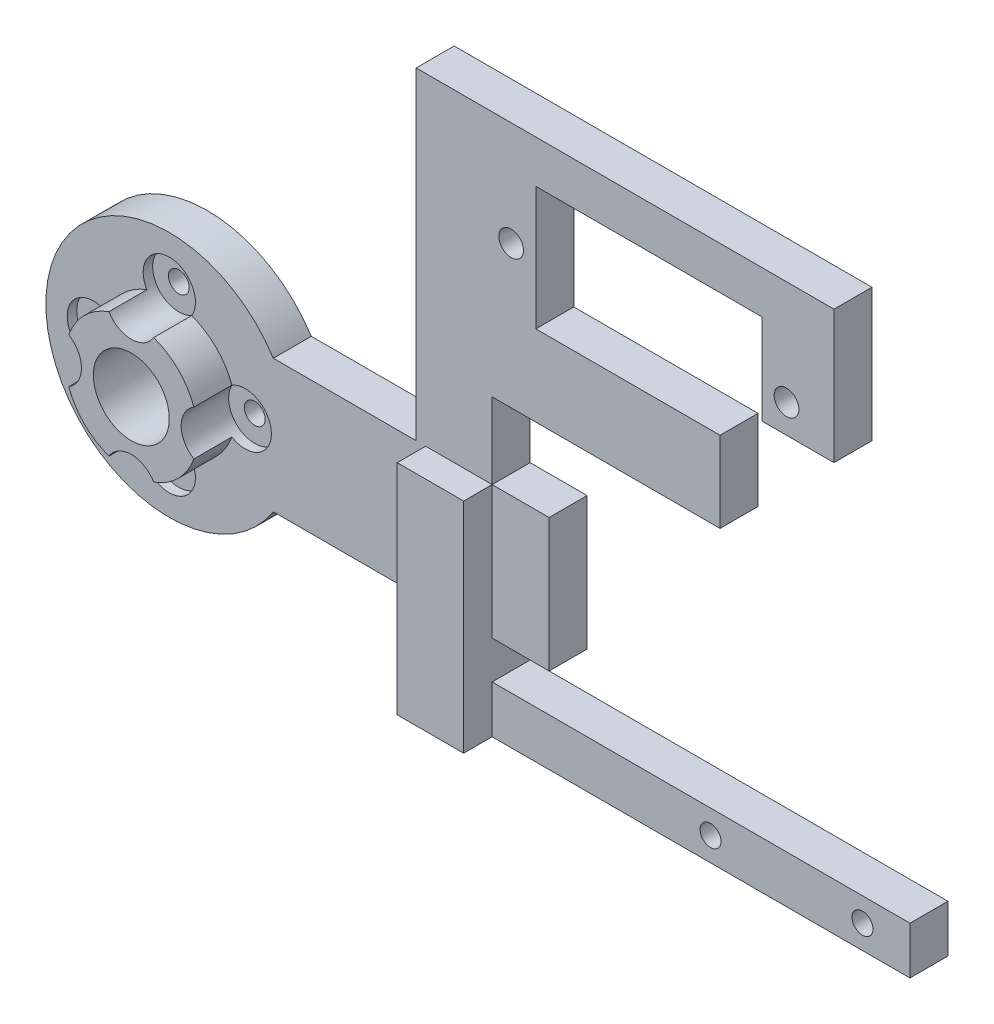
SolidWorks part; units mm, degrees
ref_plane "Front Plane" through (0, 0, 0) normal (0, 0, 1) x (1, 0, 0)
ref_plane "Top Plane" through (0, 0, 0) normal (0, 1, 0) x (1, 0, 0)
ref_plane "Right Plane" through (0, 0, 0) normal (1, 0, 0) x (0, 0, -1)
sketch "Elbow_horn_flange_profile" plane through (0, 0, 0) normal (0, 0, 1) x (1, 0, 0)
  circle A0 centre (0, 0) radius 13
  dimension "D1" = 26
extrude "Elbow_horn_flange" add sketch "Elbow_horn_flange_profile" along normal blind 4
sketch "Forearm_web_profile" plane through (0, 0, 0) normal (0, 0, 1) x (1, 0, 0)
  line L1 (0, -7) -> (40, -7)
  line L2 (0, -7) -> (0, 7)
  line L3 (0, 7) -> (40, 7)
  line L4 (40, -7) -> (40, 7)
  dimension "D1" = 40
  dimension "D2" = 14
  dimension "D3" = 7
extrude "Forearm_web" add sketch "Forearm_web_profile" along normal blind 4
sketch "Gripper_mount_rib_profile" plane through (0, 0, 0) normal (0, 0, 1) x (1, 0, 0)
  line L1 (26, 0) -> (34, 0)
  line L2 (26, 0) -> (26, 30)
  line L3 (26, 30) -> (34, 30)
  line L4 (34, 0) -> (34, 30)
  dimension "D1" = 8
  dimension "D2" = 30
  dimension "D3" = 26
extrude "Gripper_mount_rib" add sketch "Gripper_mount_rib_profile" along normal blind 4
sketch "Gripper_servo_mount_profile" plane through (0, 0, 0) normal (0, 0, 1) x (1, 0, 0)
  line L1 (26, 15) -> (70, 15)
  line L2 (26, 15) -> (26, 41)
  line L3 (26, 41) -> (70, 41)
  line L4 (70, 15) -> (70, 41)
  dimension "D1" = 44
  dimension "D2" = 26
  dimension "D3" = 26
  dimension "D4" = 15
extrude "Gripper_servo_mount" add sketch "Gripper_servo_mount_profile" along normal blind 4
sketch "Grip_SG90_body_clearance_profile" plane through (0, 0, 0) normal (0, 0, 1) x (1, 0, 0)
  line L1 (38.6, 23.5) -> (62.4, 23.5)
  line L2 (38.6, 23.5) -> (38.6, 36.5)
  line L3 (38.6, 36.5) -> (62.4, 36.5)
  line L4 (62.4, 23.5) -> (62.4, 36.5)
  dimension "D1" = 23.8
  dimension "D2" = 13
  dimension "D3" = 38.6
  dimension "D4" = 23.5
extrude "Grip_SG90_body_clearance" cut sketch "Grip_SG90_body_clearance_profile" along normal through all from offset 5
sketch "Moving_finger_sweep_relief_profile" plane through (0, 0, 0) normal (0, 0, 1) x (1, 0, 0)
  line L1 (58, 14) -> (71, 14)
  line L2 (58, 14) -> (58, 27)
  line L3 (58, 27) -> (71, 27)
  line L4 (71, 14) -> (71, 27)
  dimension "D1" = 13
  dimension "D2" = 13
  dimension "D3" = 58
  dimension "D4" = 14
extrude "Moving_finger_sweep_relief" cut sketch "Moving_finger_sweep_relief_profile" along normal through all from offset 5
sketch "Grip_servo_tab_fasteners_profile" plane through (0, 0, 0) normal (0, 0, 1) x (1, 0, 0)
  circle A0 centre (36, 30) radius 1.3
  circle A1 centre (65, 30) radius 1.3
  dimension "D1" = 2.6
  dimension "D2" = 2.6
  dimension "D3" = 36
  dimension "D4" = 65
  dimension "D5" = 30
extrude "Grip_servo_tab_fasteners" cut sketch "Grip_servo_tab_fasteners_profile" along normal through all from offset 50
sketch "Fixed_finger_spine_profile" plane through (0, 0, 0) normal (0, 0, 1) x (1, 0, 0)
  line L1 (30, -16) -> (78, -16)
  line L2 (30, -16) -> (30, -11)
  line L3 (30, -11) -> (78, -11)
  line L4 (78, -16) -> (78, -11)
  dimension "D1" = 48
  dimension "D2" = 5
  dimension "D3" = 30
  dimension "D4" = 11
extrude "Fixed_finger_spine" add sketch "Fixed_finger_spine_profile" along normal blind 4
sketch "Fixed_finger_root_profile" plane through (0, 0, 0) normal (0, 0, 1) x (1, 0, 0)
  line L1 (27, -16) -> (34, -16)
  line L2 (27, -16) -> (27, 7)
  line L3 (27, 7) -> (34, 7)
  line L4 (34, -16) -> (34, 7)
  dimension "D1" = 7
  dimension "D2" = 23
  dimension "D3" = 27
  dimension "D4" = 7
extrude "Fixed_finger_root" add sketch "Fixed_finger_root_profile" along normal blind 7
sketch "Elbow_center_screw_access_profile" plane through (0, 0, 0) normal (0, 0, 1) x (1, 0, 0)
  circle A0 centre (0, 0) radius 4
  dimension "D1" = 8
extrude "Elbow_center_screw_access" cut sketch "Elbow_center_screw_access_profile" along normal through all from offset 50
sketch "Elbow_dowel_support_hub_profile" plane through (0, 0, 0) normal (0, 0, 1) x (1, 0, 0)
  circle A0 centre (0, 0) radius 7
  circle A1 centre (0, 0) radius 4
  dimension "D1" = 14
  dimension "D2" = 8
extrude "Elbow_dowel_support_hub" add sketch "Elbow_dowel_support_hub_profile" along normal blind 4 from offset 4
sketch "Elbow_horn_fasteners_profile" plane through (0, 0, 0) normal (0, 0, 1) x (1, 0, 0)
  circle A0 centre (0, -8) radius 1.1
  circle A1 centre (0, 8) radius 1.1
  circle A2 centre (-8, 0) radius 1.1
  circle A3 centre (8, 0) radius 1.1
  dimension "D1" = 2.2
  dimension "D2" = 2.2
  dimension "D3" = 2.2
  dimension "D4" = 2.2
  dimension "D5" = 8
  dimension "D6" = 8
  dimension "D7" = 8
  dimension "D8" = 8
extrude "Elbow_horn_fasteners" cut sketch "Elbow_horn_fasteners_profile" along normal through all from offset 50
sketch "Elbow_horn_washer_recess_profile" plane through (0, 0, 0) normal (0, 0, 1) x (1, 0, 0)
  circle A0 centre (0, -8) radius 2.75
  circle A1 centre (0, 8) radius 2.75
  circle A2 centre (-8, 0) radius 2.75
  circle A3 centre (8, 0) radius 2.75
  dimension "D1" = 5.5
  dimension "D2" = 5.5
  dimension "D3" = 5.5
  dimension "D4" = 5.5
  dimension "D5" = 8
  dimension "D6" = 8
  dimension "D7" = 8
  dimension "D8" = 8
extrude "M2x8_washer_and_hub_clearance" cut sketch "Elbow_horn_washer_recess_profile" along normal blind 5 from offset 3
sketch "Fixed_pad_keeper_fasteners_profile" plane through (0, 0, 0) normal (0, 0, 1) x (1, 0, 0)
  circle A0 centre (57, -13.5) radius 1.1
  circle A1 centre (73, -13.5) radius 1.1
  dimension "D1" = 2.2
  dimension "D2" = 2.2
  dimension "D3" = 57
  dimension "D4" = 73
  dimension "D5" = 13.5
extrude "Fixed_pad_keeper_fasteners" cut sketch "Fixed_pad_keeper_fasteners_profile" along normal through all from offset 50
